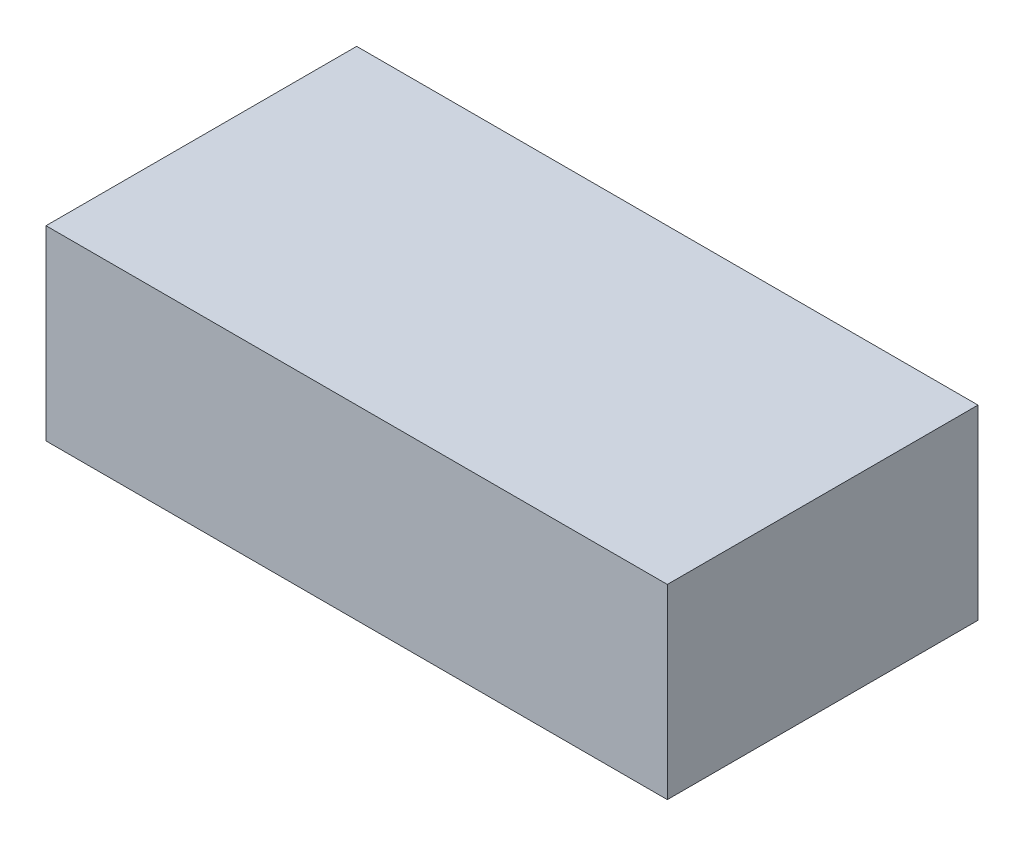
SolidWorks part; units mm, degrees
ref_plane "Front Plane" through (0, 0, 0) normal (0, 0, 1) x (1, 0, 0)
ref_plane "Top Plane" through (0, 0, 0) normal (0, 1, 0) x (1, 0, 0)
ref_plane "Right Plane" through (0, 0, 0) normal (1, 0, 0) x (0, 0, -1)
sketch "Sketch1" plane through (0, 0, 0) normal (0, 0, 1) x (1, 0, 0)
  line L1 (-115.5, 3) -> (-95.5, 3)
  line L2 (-115.5, 3) -> (-115.5, -3)
  line L3 (-115.5, -3) -> (-95.5, -3)
  line L4 (-95.5, 3) -> (-95.5, -3)
  line L5 (-115.5, 3) -> (-95.5, -3) construction
  line L6 (-115.5, -3) -> (-95.5, 3) construction
  point P0 (-105.5, 0)
  point P5 (-115.5, 0)
  dimension "D1" = 6
  dimension "D2" = 20
extrude "Boss-Extrude1" add sketch "Sketch1" along normal blind 10
